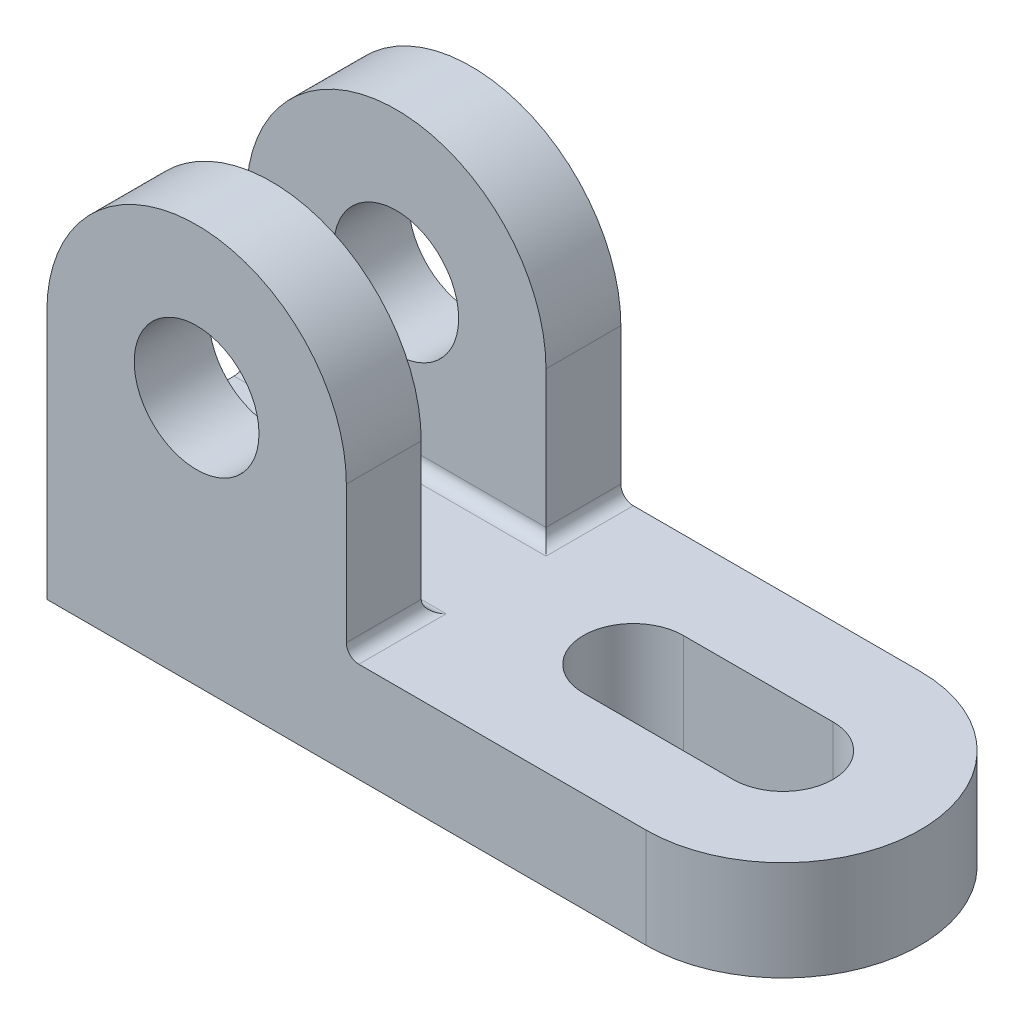
SolidWorks part; units mm, degrees
ref_plane "Front Plane" through (0, 0, 0) normal (0, 0, 1) x (1, 0, 0)
ref_plane "Top Plane" through (0, 0, 0) normal (0, 1, 0) x (1, 0, 0)
ref_plane "Right Plane" through (0, 0, 0) normal (1, 0, 0) x (0, 0, -1)
sketch "Sketch1" plane through (0, 0, 0) normal (0, 1, 0) x (1, 0, 0)
  line L1 (-59, 22) -> (37, 22)
  line L2 (-59, 22) -> (-59, -22)
  line L3 (-59, -22) -> (37, -22)
  line L5 (-59, 22) -> (49.163, -18.332) construction
  line L6 (-59, -22) -> (49.163, 18.332) construction
  arc A0 (37, -22) -> (37, 22) centre (37, 0) ccw
  point P0 (0, 0)
  point P4 (59, 0)
  point P10 (-59, 0)
  dimension "D1" = 59
  dimension "D2" = 44
  dimension "D4" = 96
  dimension "D5" = 59
extrude "Boss-Extrude1" add sketch "Sketch1" along normal blind 16
sketch "Sketch2" plane through (0, 16, 0) normal (0, 1, 0) x (1, 0, 0)
  line L0 (37, 0) -> (13, 0) construction
  line L1 (37, -8) -> (13, -8)
  line L2 (37, 8) -> (13, 8)
  arc A0 (37, -8) -> (37, 8) centre (37, 0) ccw
  arc A1 (13, 8) -> (13, -8) centre (13, 0) ccw
  point P4 (25, 0)
  dimension "D2" = 8
  dimension "D1" = 24
extrude "Cut-Extrude1" cut sketch "Sketch2" against normal up to next
sketch "Sketch3" plane through (0, 0, 22) normal (0, 0, 1) x (1, 0, 0)
  line L1 (-59, 0) -> (-11, 0)
  line L2 (-59, 0) -> (-59, 40)
  line L3 (-59, 40) -> (-11, 40)
  line L4 (-11, 0) -> (-11, 40)
  circle A0 centre (-35, 40) radius 24
  circle A1 centre (-35, 40) radius 10
  line M4 (-59, 0) -> (37, 0)
  line M6 (37, 16) -> (-59, 16)
  line M7 (-59, 16) -> (-59, 0)
  dimension "D3" = 48
  dimension "D4" = 20
  dimension "D1" = 40
  dimension "D2" = 48
extrude "Boss-Extrude2" add sketch "Sketch3" against normal blind 12 contours A0 L2 M6 | L4 M4 M6 M7 | A0 L4 M6 | A1 L3 A0 | A1 L3 A0
mirror "Mirror1" about plane through (0, 0, 0) normal (0, 0, 1) of "Boss-Extrude2"
fillet "Fillet1" radius 2 4 edges at (-35, 16, 10) (-11, 16, 16) (-11, 16, -16) (-35, 16, -10)
